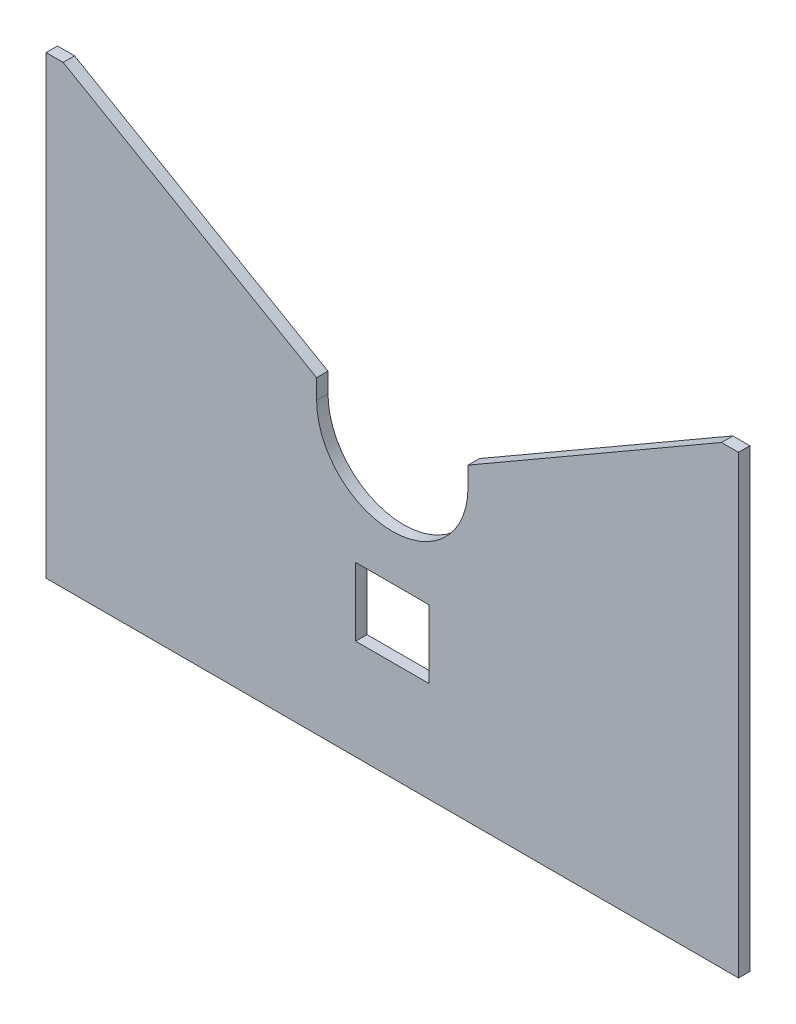
SolidWorks part; units mm, degrees
ref_plane "Front Plane" through (0, 0, 0) normal (0, 0, 1) x (1, 0, 0)
ref_plane "Top Plane" through (0, 0, 0) normal (0, 1, 0) x (1, 0, 0)
ref_plane "Right Plane" through (0, 0, 0) normal (1, 0, 0) x (0, 0, -1)
sketch "Sketch1" plane through (0, 0, 1081.9039) normal (0, 0, 1) x (1, 0, 0)
  line L0 (477.37, 579.1135) -> (743.6888, 732.8727)
  line L2 (477.37, 557.3071) -> (477.37, 579.1135)
  line L3 (743.6888, 732.8727) -> (760.1866, 742.3977)
  line L4 (760.1866, 742.3977) -> (779.2366, 742.3977)
  line L5 (392.915, 557.3071) -> (392.915, 472.8521) construction
  line L6 (779.2366, 742.3977) -> (779.2366, 234.3977)
  line L7 (779.2366, 234.3977) -> (6.5934, 234.3977)
  line L8 (25.6434, 742.3977) -> (6.5934, 742.3977)
  line L9 (42.1412, 732.8727) -> (25.6434, 742.3977)
  line L10 (6.5934, 742.3977) -> (6.5934, 234.3977)
  line L11 (308.46, 557.3071) -> (308.46, 579.1135)
  line L12 (308.46, 579.1135) -> (42.1412, 732.8727)
  circle A0 centre (392.915, 557.3071) radius 84.455 construction
  arc A1 (477.37, 557.3071) -> (308.46, 557.3071) centre (392.915, 557.3071) cw
  point P15 (392.915, 234.3977)
  dimension "D5" = 84.455
  dimension "D1" = 19.05
  dimension "D2" = 19.05
  dimension "D3" = 508
  dimension "D4" = 772.6432
extrude "Boss-Extrude1" add sketch "Sketch1" against normal blind 12.7
sketch "Sketch7" plane through (0, 0, 1069.2039) normal (0, 0, -1) x (-1, 0, 0)
  line L0 (-392.915, 557.3071) -> (-392.915, 347.9439) construction
  line L2 (-433.8235, 346.2739) -> (-352.0065, 346.2739)
  line L3 (-433.8235, 346.2739) -> (-433.8235, 422.3942)
  line L4 (-433.8235, 422.3942) -> (-352.0065, 422.3942)
  line L5 (-352.0065, 346.2739) -> (-352.0065, 422.3942)
  line L6 (-433.8235, 346.2739) -> (-352.0065, 422.3942) construction
  line L7 (-433.8235, 422.3942) -> (-352.0065, 346.2739) construction
  point P3 (-392.915, 384.334)
extrude "Cut-Extrude5" cut sketch "Sketch7" against normal up to surface (12.7 mm away) up to face at (392.915, 562.6772, 1081.9039)
